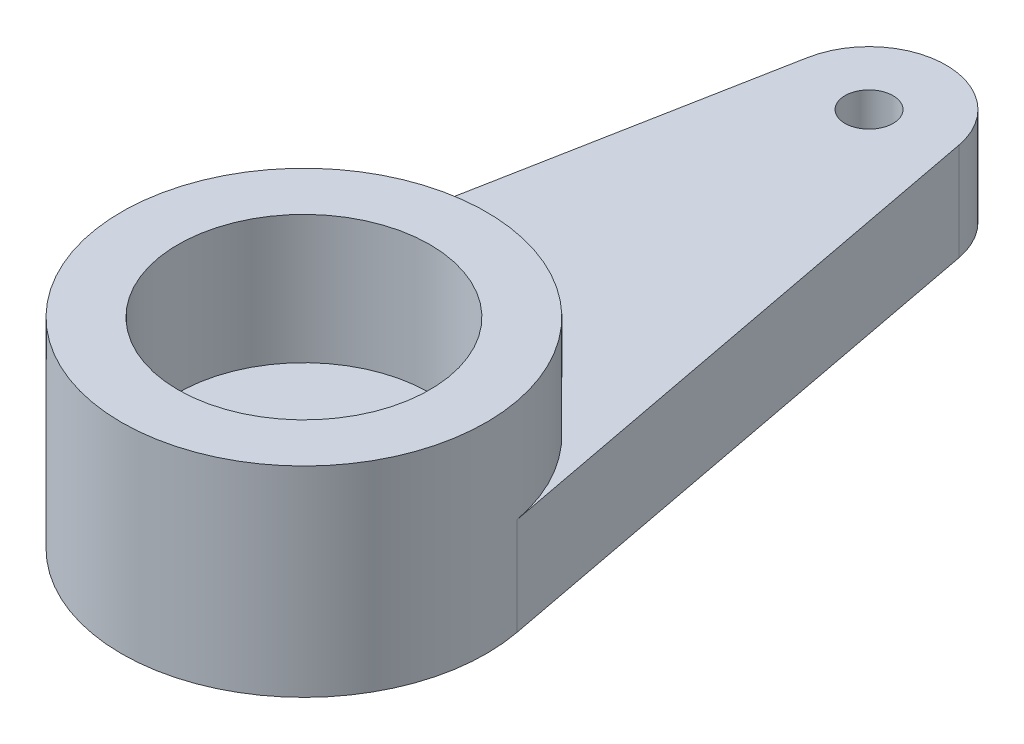
SolidWorks part; units mm, degrees
ref_plane "Front Plane" through (0, 0, 0) normal (0, 0, 1) x (1, 0, 0)
ref_plane "Top Plane" through (0, 0, 0) normal (0, 1, 0) x (1, 0, 0)
ref_plane "Right Plane" through (0, 0, 0) normal (1, 0, 0) x (0, 0, -1)
sketch "Sketch1" plane through (0, 0, 0) normal (0, 1, 0) x (1, 0, 0)
  line L0 (-3.4878, 0.6616) -> (-1.4737, 11.2795)
  line L1 (1.4737, 11.2795) -> (3.4878, 0.6616)
  arc A0 (-3.4878, 0.6616) -> (3.4878, 0.6616) centre (0, 0) ccw
  arc A1 (-1.4737, 11.2795) -> (1.4737, 11.2795) centre (0, 11) cw
  dimension "D2" = 7.1
  dimension "D3" = 1.5
  dimension "D1" = 11
extrude "Boss-Extrude1" add sketch "Sketch1" along normal blind 1.9
sketch "Sketch2" plane through (0, 1.9, 0) normal (0, 1, 0) x (1, 0, 0)
  circle A0 centre (0, 0) radius 3.55
  circle A1 centre (0, 0) radius 2.45
  arc A2 (-3.4878, 0.6616) -> (3.4878, 0.6616) centre (0, 0) ccw construction
  dimension "D1" = 4.9
extrude "Boss-Extrude2" add sketch "Sketch2" along normal blind 2
sketch "Sketch3" plane through (0, 3.9, 0) normal (0, 1, 0) x (1, 0, 0)
  circle A0 centre (0, 0) radius 2.45 construction
  circle A1 centre (0, 0) radius 2.45
extrude "Cut-Extrude1" cut sketch "Sketch3" against normal blind 2.5
sketch "Sketch4" plane through (0, 1.4, 0) normal (0, 1, 0) x (1, 0, 0)
  circle A0 centre (0, 0) radius 0.8819
  circle A1 centre (0, 11) radius 0.4685
  arc A2 (1.4737, 11.2795) -> (-1.4737, 11.2795) centre (0, 11) ccw construction
extrude "Cut-Extrude2" cut sketch "Sketch4" against normal through all both and the other way through all contours A1 | A0
